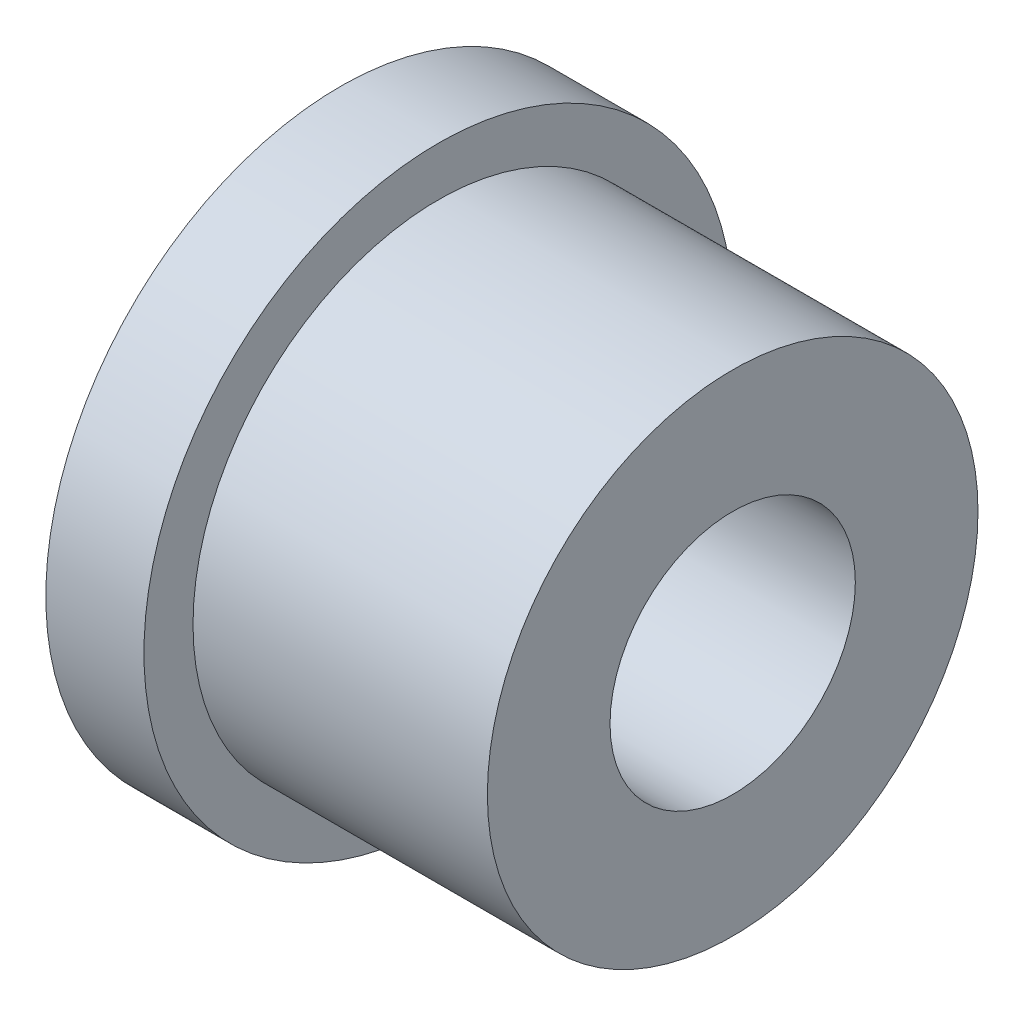
SolidWorks part; units mm, degrees
material "Brass"
ref_plane "Front Plane" through (0, 0, 0) normal (0, 0, 1) x (1, 0, 0)
ref_plane "Top Plane" through (0, 0, 0) normal (0, 1, 0) x (1, 0, 0)
ref_plane "Right Plane" through (0, 0, 0) normal (1, 0, 0) x (0, 0, -1)
sketch "Sketch1" plane through (0, 0, 0) normal (1, 0, 0) x (0, 0, -1)
  circle A0 centre (0, 0) radius 6
  circle A1 centre (0, 0) radius 2.5
  dimension "D1" = 12
  dimension "D2" = 5
extrude "Boss-Extrude1" add sketch "Sketch1" along normal blind 2
sketch "Sketch2" plane through (2, 0, 0) normal (1, 0, 0) x (0, 0, -1)
  circle A0 centre (0, 0) radius 5
  circle A1 centre (0, 0) radius 2.5
  dimension "D1" = 10
  dimension "D2" = 5
extrude "Boss-Extrude2" add sketch "Sketch2" along normal blind 6
